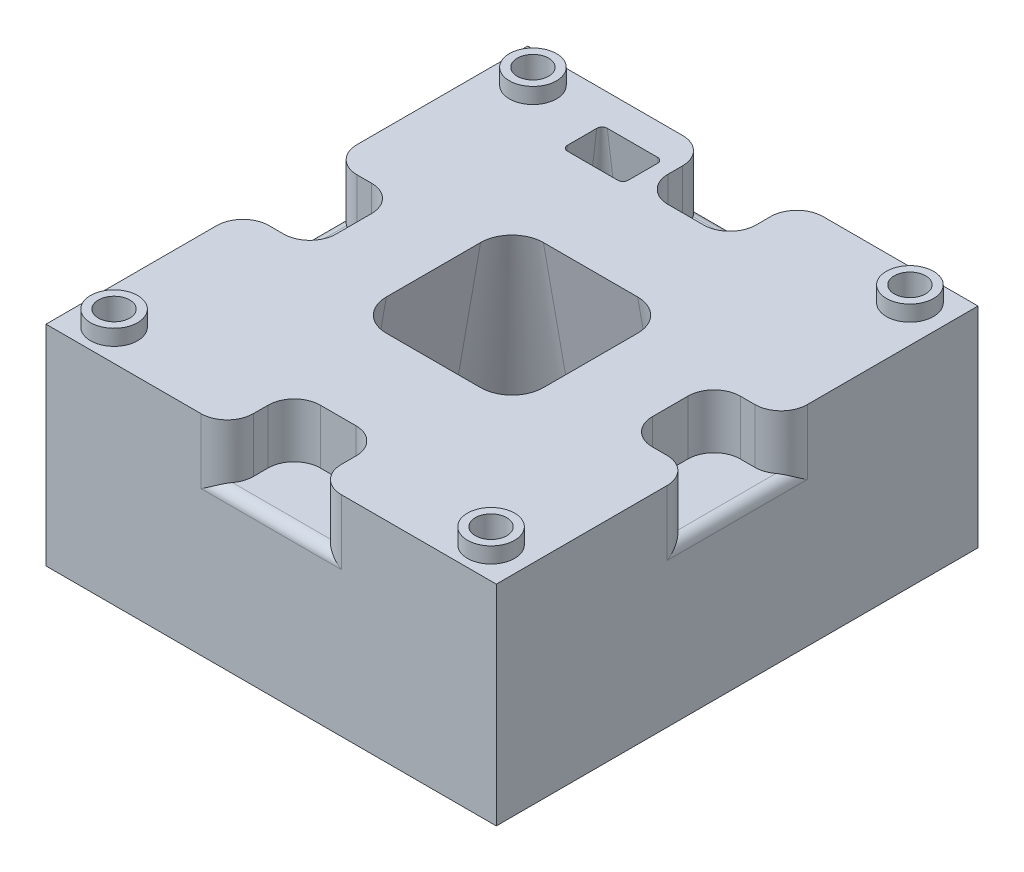
SolidWorks part; units mm, degrees
ref_plane "Plan de face" through (0, 0, 0) normal (0, 0, 1) x (1, 0, 0)
ref_plane "Plan de dessus" through (0, 0, 0) normal (0, 1, 0) x (1, 0, 0)
ref_plane "Plan de droite" through (0, 0, 0) normal (1, 0, 0) x (0, 0, -1)
sketch "Esquisse1" plane through (0, 0, 0) normal (0, 1, 0) x (1, 0, 0)
  line L0 (-19, 4.2) -> (-17.6, 4.2)
  line L1 (-19, 23) -> (-6.7, 23)
  line L2 (-21.5, 20.5) -> (-21.5, 6.7)
  line L3 (-19, -23) -> (-6.7, -23)
  line L4 (21.5, 20.5) -> (21.5, 6.7)
  line L5 (-21.5, 23) -> (21.5, -23) construction
  line L6 (-21.5, -23) -> (21.5, 23) construction
  line L7 (-15.1, 1.7) -> (-15.1, -1.7)
  line L8 (-17.6, -4.2) -> (-19, -4.2)
  line L9 (-4.2, 20.5) -> (-4.2, 19.1)
  line L10 (-1.7, 16.6) -> (1.7, 16.6)
  line L11 (4.2, 19.1) -> (4.2, 20.5)
  line L12 (19, 4.2) -> (17.6, 4.2)
  line L13 (15.1, 1.7) -> (15.1, -1.7)
  line L14 (17.6, -4.2) -> (19, -4.2)
  line L15 (-4.2, -20.5) -> (-4.2, -19.1)
  line L16 (-1.7, -16.6) -> (1.7, -16.6)
  line L17 (4.2, -19.1) -> (4.2, -20.5)
  line L18 (6.7, 23) -> (19, 23)
  line L19 (21.5, -6.7) -> (21.5, -20.5)
  line L20 (6.7, -23) -> (19, -23)
  line L21 (-21.5, -6.7) -> (-21.5, -20.5)
  line L22 (-21.5, -20.5) -> (-21.5, -23)
  line L23 (-21.5, -23) -> (-19, -23)
  line L24 (19, -23) -> (21.5, -23)
  line L25 (21.5, -23) -> (21.5, -20.5)
  line L26 (19, 23) -> (21.5, 23)
  line L27 (21.5, 23) -> (21.5, 20.5)
  line L28 (-19, 23) -> (-21.5, 23)
  line L29 (-21.5, 23) -> (-21.5, 20.5)
  circle A0 centre (-18, 20) radius 1.5
  circle A1 centre (18, 20) radius 1.5
  circle A2 centre (18, -20) radius 1.5
  circle A3 centre (-18, -20) radius 1.5
  arc A4 (19, 4.2) -> (21.5, 6.7) centre (19, 6.7) ccw
  arc A6 (6.7, 23) -> (4.2, 20.5) centre (6.7, 20.5) ccw
  arc A7 (-4.2, 20.5) -> (-6.7, 23) centre (-6.7, 20.5) ccw
  arc A9 (-21.5, 6.7) -> (-19, 4.2) centre (-19, 6.7) ccw
  arc A10 (-19, -4.2) -> (-21.5, -6.7) centre (-19, -6.7) ccw
  arc A12 (-4.2, -20.5) -> (-6.7, -23) centre (-6.7, -20.5) cw
  arc A13 (4.2, -20.5) -> (6.7, -23) centre (6.7, -20.5) ccw
  arc A15 (21.5, -6.7) -> (19, -4.2) centre (19, -6.7) ccw
  arc A16 (4.2, 19.1) -> (1.7, 16.6) centre (1.7, 19.1) cw
  arc A17 (-1.7, 16.6) -> (-4.2, 19.1) centre (-1.7, 19.1) cw
  arc A18 (-17.6, 4.2) -> (-15.1, 1.7) centre (-17.6, 1.7) cw
  arc A19 (-15.1, -1.7) -> (-17.6, -4.2) centre (-17.6, -1.7) cw
  arc A20 (15.1, 1.7) -> (17.6, 4.2) centre (17.6, 1.7) cw
  arc A21 (15.1, -1.7) -> (17.6, -4.2) centre (17.6, -1.7) ccw
  arc A22 (4.2, -19.1) -> (1.7, -16.6) centre (1.7, -19.1) ccw
  arc A23 (-1.7, -16.6) -> (-4.2, -19.1) centre (-1.7, -19.1) ccw
  point P0 (0, 0)
  point P37 (4.2, 23)
  point P40 (-4.2, 23)
  point P46 (-21.5, 4.2)
  point P49 (-21.5, -4.2)
  point P55 (-4.2, -23)
  point P58 (4.2, -23)
  point P64 (21.5, -4.2)
  point P69 (-4.2, 16.6)
  point P72 (-15.1, 4.2)
  point P75 (-15.1, -4.2)
  point P80 (15.1, -4.2)
  point P83 (4.2, -16.6)
  dimension "D3" = 3
  dimension "D4" = 3
  dimension "D5" = 3
  dimension "D6" = 3
  dimension "D21" = 2.5
  dimension "D1" = 46
  dimension "D2" = 43
  dimension "D7" = 36
  dimension "D8" = 36
  dimension "D9" = 17.3
  dimension "D10" = 17.3
  dimension "D11" = 6.4
  dimension "D12" = 18.8
  dimension "D13" = 18.8
  dimension "D14" = 6.4
  dimension "D15" = 6.4
  dimension "D16" = 18.8
  dimension "D17" = 18.8
  dimension "D18" = 17.3
  dimension "D19" = 17.3
  dimension "D20" = 6.4
  dimension "D22" = 3.5
  dimension "D23" = 3
  dimension "D24" = 3.5
  dimension "D25" = 3
extrude "Boss.-Extru.1" add sketch "Esquisse1" along normal blind 20
sketch "Esquisse2" plane through (0, 20, 0) normal (0, 1, 0) x (1, 0, 0)
  circle A0 centre (-18, 20) radius 2.25
  circle A2 centre (18, 20) radius 2.25
  circle A3 centre (18, -20) radius 2.25
  circle A4 centre (-18, -20) radius 2.25
  circle A5 centre (-18, 20) radius 1.5 construction
  circle A6 centre (18, 20) radius 1.5 construction
  circle A7 centre (18, -20) radius 1.5 construction
  circle A8 centre (-18, -20) radius 1.5 construction
  circle A9 centre (-18, 20) radius 1.5
  circle A10 centre (18, 20) radius 1.5
  circle A11 centre (18, -20) radius 1.5
  circle A12 centre (-18, -20) radius 1.5
  dimension "D1" = 4.5
  dimension "D2" = 4.5
  dimension "D3" = 4.5
  dimension "D4" = 4.5
extrude "Boss.-Extru.2" add sketch "Esquisse2" along normal blind 1.5
sketch "Esquisse6" plane through (0, 0, 0) normal (0, -1, 0) x (1, 0, 0)
  line L0 (-21.5, 6.7) -> (-21.5, 23) construction
  line L1 (-21.5, 9.5229) -> (-14.2843, 9.5229)
  line L2 (-21.5, 9.5229) -> (-21.5, -8.8427)
  line L3 (-21.5, -8.8427) -> (-14.2843, -8.8427)
  line L4 (-14.2843, 9.5229) -> (-14.2843, -8.8427)
  line L5 (-21.5, 23) -> (-6.7, 23) construction
  line L6 (-8.3892, 23) -> (7.4067, 23)
  line L7 (-8.3892, 23) -> (-8.3892, 15.8715)
  line L8 (-8.3892, 15.8715) -> (7.4067, 15.8715)
  line L9 (7.4067, 23) -> (7.4067, 15.8715)
  line L10 (21.5, 23) -> (21.5, 6.7) construction
  line L11 (21.5, 11.3368) -> (14.511, 11.3368)
  line L12 (21.5, 11.3368) -> (21.5, -8.8427)
  line L13 (21.5, -8.8427) -> (14.511, -8.8427)
  line L14 (14.511, 11.3368) -> (14.511, -8.8427)
  line L15 (-4.2, -19.1) -> (-4.2, -20.5) construction
  line L16 (-4.2, -19.1) -> (-4.2, -20.5)
  line L17 (-6.7, -23) -> (8.6915, -23)
  line L18 (21.5, -23) -> (6.7, -23) construction
  line L19 (8.6915, -23) -> (8.6915, -16.6)
  line L20 (8.6915, -16.6) -> (-1.7, -16.6)
  arc A0 (-6.7, -23) -> (-4.2, -20.5) centre (-6.7, -20.5) ccw construction
  arc A1 (-1.7, -16.6) -> (-4.2, -19.1) centre (-1.7, -19.1) ccw construction
  arc A2 (-6.7, -23) -> (-4.2, -20.5) centre (-6.7, -20.5) ccw
  arc A3 (-1.7, -16.6) -> (-4.2, -19.1) centre (-1.7, -19.1) ccw
extrude "Boss.-Extru.3" add sketch "Esquisse6" against normal blind 14.8
sketch "Esquisse3" plane through (0, 20, 0) normal (0, 1, 0) x (1, 0, 0)
  line L1 (-4.5, 7.5) -> (4.5, 7.5)
  line L2 (-7.5, 4.5) -> (-7.5, -4.5)
  line L3 (-4.5, -7.5) -> (4.5, -7.5)
  line L4 (7.5, 4.5) -> (7.5, -4.5)
  line L5 (-7.5, 7.5) -> (7.5, -7.5) construction
  line L6 (-7.5, -7.5) -> (7.5, 7.5) construction
  arc A0 (4.5, -7.5) -> (7.5, -4.5) centre (4.5, -4.5) ccw
  arc A1 (-7.5, -4.5) -> (-4.5, -7.5) centre (-4.5, -4.5) ccw
  arc A2 (-4.5, 7.5) -> (-7.5, 4.5) centre (-4.5, 4.5) ccw
  arc A3 (7.5, 4.5) -> (4.5, 7.5) centre (4.5, 4.5) ccw
  point P0 (0, 0)
  dimension "D3" = 3
  dimension "D1" = 15
  dimension "D2" = 15
extrude "Enlèv. mat.-Extru.1" cut sketch "Esquisse3" against normal up to next (20 mm away) draft 10 draft outward yes
sketch "Esquisse4" plane through (0, 20, 0) normal (0, 1, 0) x (1, 0, 0)
  line L0 (-21.5, 23) -> (-21.5, 6.7) construction
  line L1 (-10.9, 20) -> (-6.1, 20)
  line L2 (-11.4, 19.5) -> (-11.4, 16.7)
  line L3 (-10.9, 16.2) -> (-6.1, 16.2)
  line L4 (-5.6, 19.5) -> (-5.6, 16.7)
  line L5 (-11.4, 20) -> (-5.6, 16.2) construction
  line L6 (-11.4, 16.2) -> (-5.6, 20) construction
  line L7 (-6.7, 23) -> (-21.5, 23) construction
  arc A0 (-6.1, 16.2) -> (-5.6, 16.7) centre (-6.1, 16.7) ccw
  arc A1 (-6.1, 20) -> (-5.6, 19.5) centre (-6.1, 19.5) cw
  arc A2 (-10.9, 16.2) -> (-11.4, 16.7) centre (-10.9, 16.7) cw
  arc A3 (-11.4, 19.5) -> (-10.9, 20) centre (-10.9, 19.5) cw
  point P0 (-8.5, 18.1)
  dimension "D5" = 0.5
  dimension "D1" = 13
  dimension "D2" = 4.9
  dimension "D3" = 3.8
  dimension "D4" = 5.8
extrude "Enlèv. mat.-Extru.2" cut sketch "Esquisse4" against normal up to surface (20 mm away) draft 7
sketch "Esquisse5" plane through (0, 0, 0) normal (0, -1, 0) x (1, 0, 0)
  circle A0 centre (-18, 20) radius 2.5
  circle A1 centre (18, 20) radius 2.5
  circle A2 centre (18, -20) radius 2.5
  circle A3 centre (-18, -20) radius 2.5
  circle A4 centre (-18, -20) radius 1.5 construction
  dimension "D1" = 5
  dimension "D2" = 5
  dimension "D3" = 5
  dimension "D4" = 5
extrude "Enlèv. mat.-Extru.3" cut sketch "Esquisse5" against normal blind 18
fillet "Congé4" radius 1 1 edges at (-21.5, 14.8, 0)
fillet "Congé5" radius 1 1 edges at (0, 14.8, 23)
fillet "Congé6" radius 1 1 edges at (21.5, 14.8, 0)
fillet "Congé7" radius 1 1 edges at (0, 14.8, -23)
